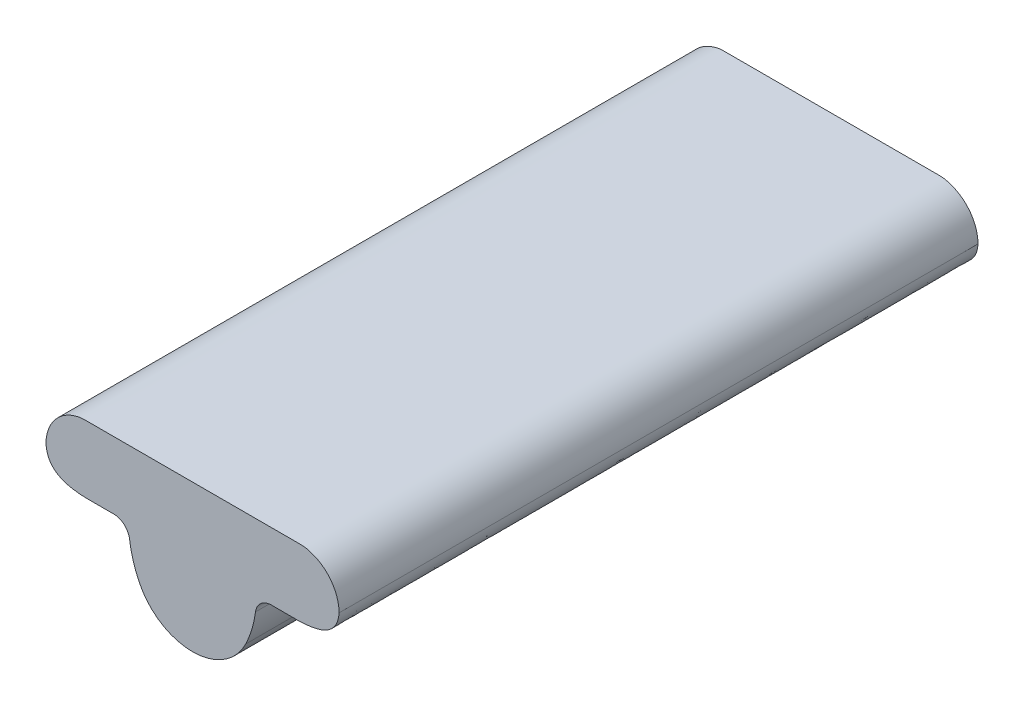
SolidWorks part; units mm, degrees
material "CA"
ref_plane "Спереди" through (0, 0, 0) normal (0, 0, 1) x (1, 0, 0)
ref_plane "Сверху" through (0, 0, 0) normal (0, 1, 0) x (1, 0, 0)
ref_plane "Справа" through (0, 0, 0) normal (1, 0, 0) x (0, 0, -1)
sketch "Sketch1" plane through (0, 0, 0) normal (0, 0, 1) x (1, 0, 0)
  line L0 (1.6786, 0) -> (-2.4977, 0) construction
  line L1 (0, 0.7721) -> (0, -0.7654) construction
  line L2 (-1, 0.376) -> (1, 0.376) construction
  line L3 (-1.8592, -1.004) -> (1.8771, -1.004) construction
  line L4 (-1, 0.5984) -> (-1, -0.5097) construction
  line L5 (1, 0.5984) -> (1, -0.5097) construction
  line L6 (-1, -0.254) -> (-0.7402, -0.254)
  line L7 (1, -0.254) -> (0.7402, -0.254)
  arc A0 (-0.4989, -0.6922) -> (0.4989, -0.6922) centre (0, -0.449) ccw
  arc A1 (-0.5915, -0.3844) -> (-0.7402, -0.254) centre (-0.7402, -0.404) ccw
  arc A2 (-1, 0.376) -> (-1.376, 0) centre (-1, 0) ccw construction
  arc A3 (-0.5915, -0.3844) -> (-0.4989, -0.6922) centre (0.4, -0.254) ccw
  arc A4 (0.5915, -0.3844) -> (0.4989, -0.6922) centre (-0.4, -0.254) cw
  arc A5 (0.5915, -0.3844) -> (0.7402, -0.254) centre (0.7402, -0.404) cw
  arc A6 (1, 0.376) -> (1.376, 0) centre (1, 0) cw construction
  spline S0 degree 3 poles (-1.376, 0) (-1.3623, -0.2216) (-1.1514, -0.2486) (-1, -0.254) knots 0 0 0 0 1 1 1 1
  spline S1 degree 3 poles (1.376, 0) (1.3623, -0.2216) (1.1514, -0.2486) (1, -0.254) knots 0 0 0 0 1 1 1 1
  spline S2 degree 3 poles (-1.376, 0) (-1.376, 0.1569) (-1.2888, 0.2873) (-1.1439, 0.3474) (-1.1288, 0.3536) (-1.0979, 0.3641) (-1.0489, 0.376) (-1.0163, 0.376) (-1, 0.376) (-0.9837, 0.376) (-0.9511, 0.376) (-0.9022, 0.376) (-0.8696, 0.376) (-0.8533, 0.376) (-0.2844, 0.376) (0.2844, 0.376) (0.8533, 0.376) (0.8696, 0.376) (0.9022, 0.376) (0.9511, 0.376) (0.9837, 0.376) (1, 0.376) (1.0163, 0.376) (1.0489, 0.376) (1.0979, 0.3641) (1.1288, 0.3536) (1.1439, 0.3474) (1.2888, 0.2873) (1.376, 0.1569) (1.376, 0) knots 0 0 0 0 0.133522 0.133522 0.133522 0.149151 0.16478 0.180408 0.180408 0.180408 0.196037 0.211666 0.227295 0.227295 0.227295 0.772705 0.772705 0.772705 0.788334 0.803963 0.819592 0.819592 0.819592 0.83522 0.850849 0.866478 0.866478 0.866478 1 1 1 1 weights 1 0.887646 0.887646 1 1 1 1 1 1 1 1 1 1 1 1 1 1 1 1 1 1 1 1 1 1 1 1 0.887646 0.887646 1
  dimension "D4" = 1.11
  dimension "D5" = 0.3
  dimension "D6" = 0.4
  dimension "D7" = 1
  dimension "D1" = 0.376
  dimension "D2" = 1.38
  dimension "D3" = 2
  dimension "D9" = 0.254
extrude "Boss-Extrude1" add sketch "Sketch1" along normal blind 6 contours S1 L7 A5 A4 A0 A3 A1 L6 S0 S2
sketch "Sketch3" plane through (0, 0, 0) normal (0, 1, 0) x (1, 0, 0)
  line L0 (-1, 0.2254) -> (-1, -1.423) construction
  line L1 (1, 0.2254) -> (1, -1.423) construction
  line L2 (0, 0) -> (0, -0.6343) construction
  dimension "D1" = 2
